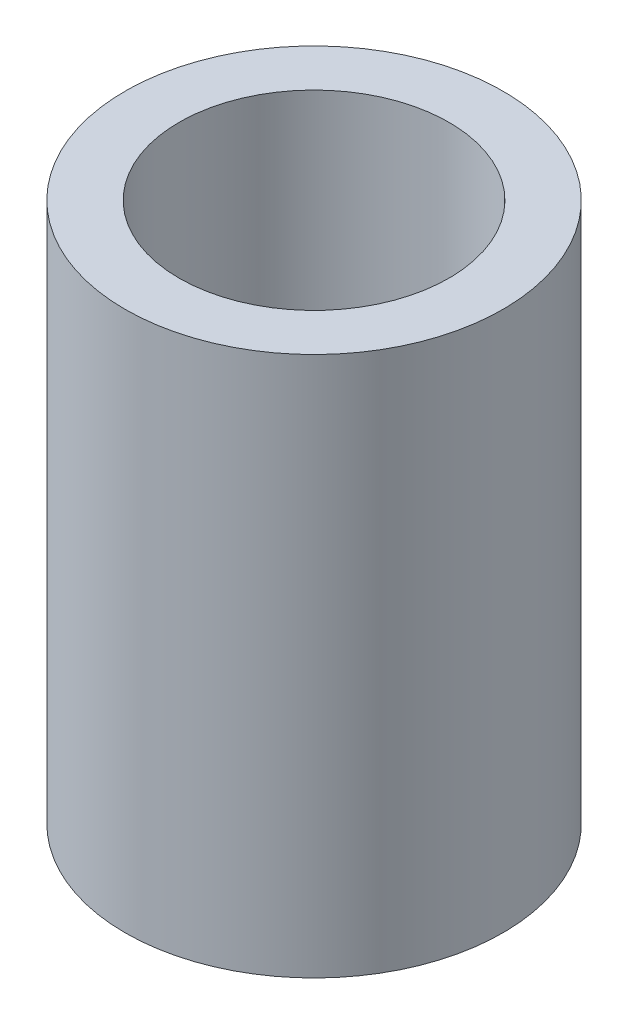
SolidWorks part; units mm, degrees
ref_plane "Front Plane" through (0, 0, 0) normal (0, 0, 1) x (1, 0, 0)
ref_plane "Top Plane" through (0, 0, 0) normal (0, 1, 0) x (1, 0, 0)
ref_plane "Right Plane" through (0, 0, 0) normal (1, 0, 0) x (0, 0, -1)
sketch "Sketch1" plane through (0, 0, 0) normal (0, 1, 0) x (1, 0, 0)
  circle A0 centre (0, 0) radius 2.5
  circle A1 centre (0, 0) radius 3.5
  dimension "D1" = 5
  dimension "D2" = 7
extrude "Boss-Extrude1" add sketch "Sketch1" along normal blind 10
